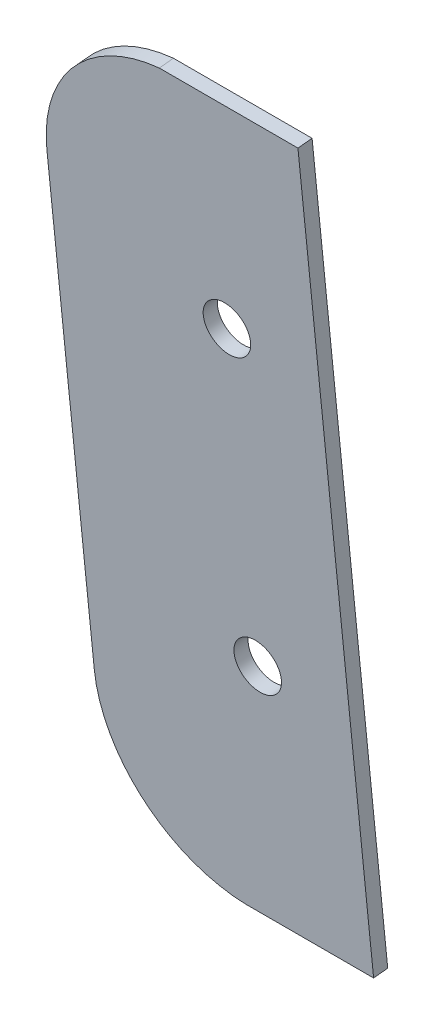
SolidWorks part; units mm, degrees
ref_plane "Front Plane" through (0, 0, 0) normal (0, 0, 1) x (1, 0, 0)
ref_plane "Top Plane" through (0, 0, 0) normal (0, 1, 0) x (1, 0, 0)
ref_plane "Right Plane" through (0, 0, 0) normal (1, 0, 0) x (0, 0, -1)
sketch "Sketch1" plane through (0, 7.783, -77.8297) normal (0, -0.0995, 0.995) x (1, 0, 0)
  line L4 (-22.0566, -7.8114) -> (-8.5, -7.8114)
  line L5 (-8.5, -7.8114) -> (-8.5, 72.4868)
  line L6 (-8.5, 72.4868) -> (-23.1401, 72.4868)
  line L7 (-36.5, 57.5024) -> (-36.5, 7.253)
  line L8 (-22.0566, -7.8114) -> (-8.5, -7.8114)
  line L9 (-8.5, -7.8114) -> (-8.5, 72.4868)
  line L10 (-8.5, 72.4868) -> (-23.1401, 72.4868)
  line L11 (-36.5, 57.5024) -> (-36.5, 7.253)
  ellipse E3 centre (-21.5, 7.253) end of major axis (-21.5, -7.8218) minor radius 15 (-36.5, 7.253) -> (-22.0566, -7.8114) ccw
  ellipse E4 centre (-21.5, 57.5024) end of major axis (-21.5, 42.4276) minor radius 15 (-23.1401, 72.4868) -> (-35.9345, 61.6026) ccw
  ellipse E5 centre (-21.5, 57.5024) end of major axis (-21.5, 72.5772) minor radius 15 (-35.9345, 61.6026) -> (-36.5, 57.5024) ccw
  ellipse E6 centre (-21.5, 7.253) end of major axis (-21.5, -7.8218) minor radius 15 (-36.5, 7.253) -> (-22.0566, -7.8114) ccw
  ellipse E7 centre (-21.5, 57.5024) end of major axis (-21.5, 42.4276) minor radius 15 (-23.1401, 72.4868) -> (-35.9345, 61.6026) ccw
  ellipse E8 centre (-21.5, 57.5024) end of major axis (-21.5, 72.5772) minor radius 15 (-35.9345, 61.6026) -> (-36.5, 57.5024) ccw
  dimension "D1" = 0
extrude "Boss-Extrude2" add sketch "Sketch1" along normal blind 1.5
sketch "Sketch2" plane through (0, 7.783, -77.8297) normal (0, 0.0995, -0.995) x (-1, 0, 0)
  ellipse E0 centre (18.25, 17.1942) end of major axis (18.25, 19.7067) minor radius 2.5 construction
  ellipse E1 centre (18.25, 49.8563) end of major axis (18.25, 52.3688) minor radius 2.5 construction
  ellipse E2 centre (18.25, 17.1942) end of major axis (18.25, 19.7067) minor radius 2.5
  ellipse E3 centre (18.25, 49.8563) end of major axis (18.25, 52.3688) minor radius 2.5
extrude "Cut-Extrude1" cut sketch "Sketch2" against normal through all
